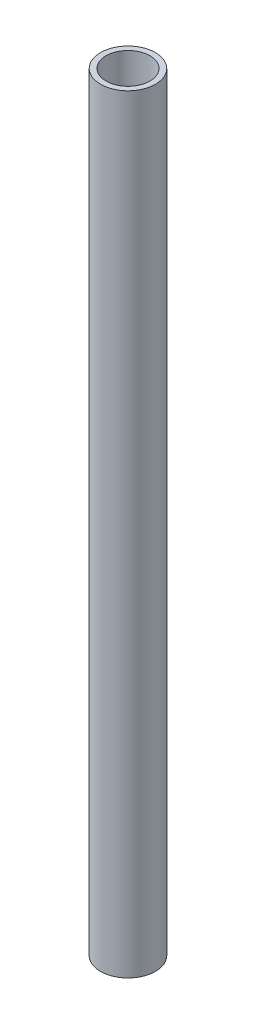
SolidWorks part; units mm, degrees
ref_plane "Front Plane" through (0, 0, 0) normal (0, 0, 1) x (1, 0, 0)
ref_plane "Top Plane" through (0, 0, 0) normal (0, 1, 0) x (1, 0, 0)
ref_plane "Right Plane" through (0, 0, 0) normal (1, 0, 0) x (0, 0, -1)
sketch "Sketch1" plane through (0, 0, 0) normal (0, 1, 0) x (1, 0, 0)
  circle A0 centre (0, 0) radius 0.25
  circle A1 centre (0, 0) radius 0.2
extrude "Boss-Extrude1" add sketch "Sketch1" along normal blind 7
